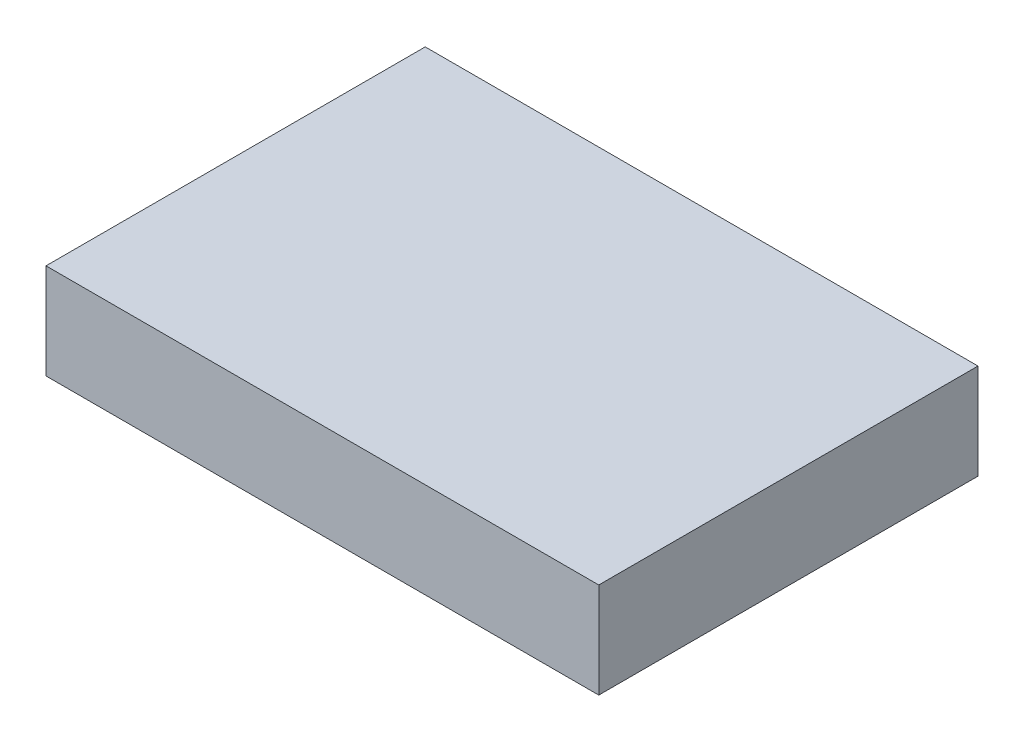
SolidWorks part; units mm, degrees
ref_plane "Front Plane" through (0, 0, 0) normal (0, 0, 1) x (1, 0, 0)
ref_plane "Top Plane" through (0, 0, 0) normal (0, 1, 0) x (1, 0, 0)
ref_plane "Right Plane" through (0, 0, 0) normal (1, 0, 0) x (0, 0, -1)
sketch "Sketch6" plane through (0, 0, 0) normal (0, 1, 0) x (1, 0, 0)
  line L1 (0, 0) -> (147.1919, 0)
  line L2 (0, 0) -> (0, 100.9795)
  line L3 (0, 100.9795) -> (147.1919, 100.9795)
  line L4 (147.1919, 0) -> (147.1919, 100.9795)
extrude "Extrude1" add sketch "Sketch6" along normal blind 25.4
sketch "Sketch7" plane through (0, 0, 0) normal (0, 1, 0) x (1, 0, 0)
  circle A0 centre (70.9559, 51.9748) radius 19.0472
